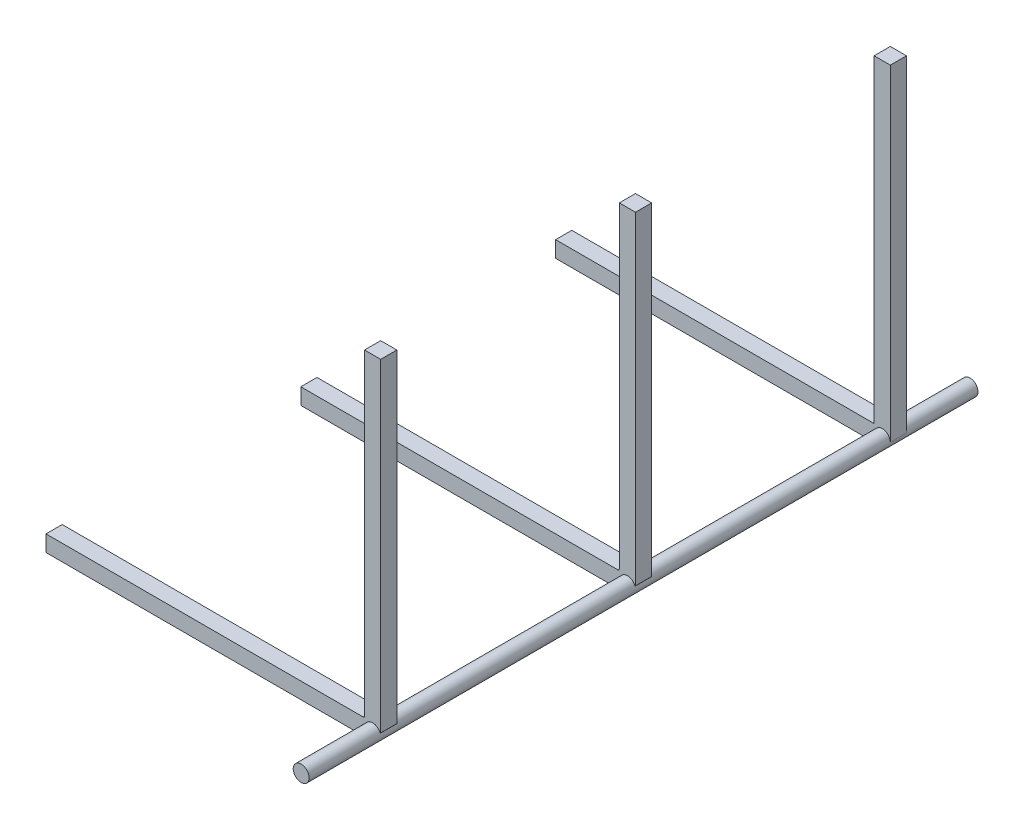
SolidWorks part; units mm, degrees
ref_plane "前视基准面" through (0, 0, 0) normal (0, 0, 1) x (1, 0, 0)
ref_plane "上视基准面" through (0, 0, 0) normal (0, 1, 0) x (1, 0, 0)
ref_plane "右视基准面" through (0, 0, 0) normal (1, 0, 0) x (0, 0, -1)
sketch "草图1" plane through (0, 0, 0) normal (0, 0, 1) x (1, 0, 0)
  circle A0 centre (0, 0) radius 25
  point P3 (0, 0)
  dimension "D1" = 50
extrude "凸台-拉伸1" add sketch "草图1" along normal blind 2100
ref_plane "基准面1" through (0, 0, 1850) normal (0, 0, 1) x (1, 0, 0)
sketch "草图2" plane through (0, 0, 1850) normal (0, 0, 1) x (1, 0, 0)
  line L2 (0, 0) -> (0, 75.82) construction
  line L4 (0, 0) -> (-20.6285, 20.6285) construction
  line L8 (25, 0) -> (25, 1025.8)
  line L9 (25, 1025.8) -> (-25.8, 1025.8)
  line L10 (-25.8, 1025.8) -> (-25.8, 25.8)
  line L11 (0, -25) -> (-1025.8, -25)
  line L12 (-1025.8, 25.8) -> (-25.8, 25.8)
  line L13 (-1025.8, -25) -> (-1025.8, 25.8)
  arc A1 (0, -25) -> (25, 0) centre (0, 0) cw
  circle A2 centre (0, 0) radius 25 construction
  point P4 (-20.6285, -13.3165)
  point P10 (0, 816.9617)
  point P12 (20.6285, 11.5107)
  point P15 (-63.3908, 67.7856)
  point P16 (0, 0)
  point P17 (-49.8111, 65.7281)
  point P18 (-25, 25)
  point P19 (-26.2894, 26.2894)
  point P20 (-31.0138, 31.0138)
  point P21 (25, 0)
  dimension "D1" = 90
  dimension "D2" = 45
  dimension "D3" = 50.8
  dimension "D5" = 1000
extrude "凸台-拉伸2" add sketch "草图2" along normal mid plane 50.8 separate body
fillet "圆角8" radius 1 2 edges at (0, -25, 1850) (25, 0, 1850)
fillet "圆角9" radius 5 1 edges at (-25.8, 25.8, 1850)
pattern_linear "阵列(线性)4" count 3 spacing 800 along (0, 0, -1) of "凸台-拉伸2"
fillet "圆角10" radius 1 2 edges at (0, -25, 1050) (25, 0, 1050)
fillet "圆角11" radius 5 1 edges at (-25.8, 25.8, 1050)
